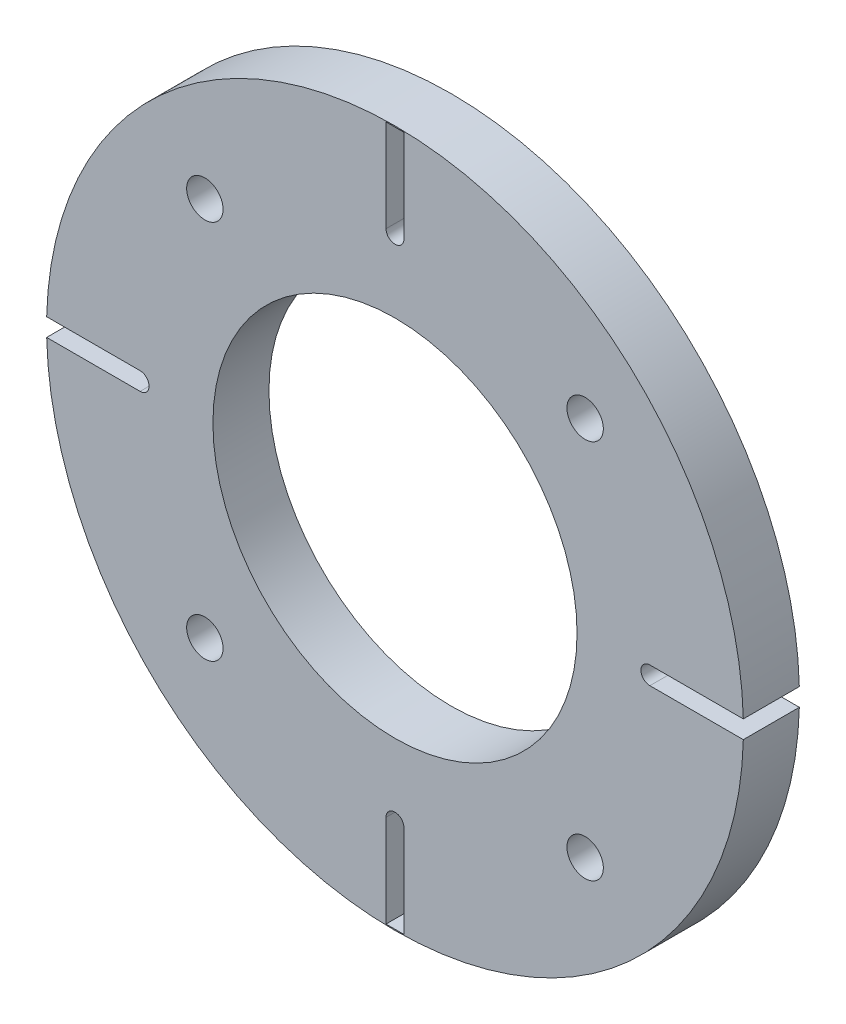
SolidWorks part; units mm, degrees
ref_plane "Ön Düzlem" through (0, 0, 0) normal (0, 0, 1) x (1, 0, 0)
ref_plane "Üst Düzlem" through (0, 0, 0) normal (0, 1, 0) x (1, 0, 0)
ref_plane "Sağ Düzlem" through (0, 0, 0) normal (1, 0, 0) x (0, 0, -1)
sketch "Çizim1" plane through (0, 0, 0) normal (0, 0, 1) x (1, 0, 0)
  circle A0 centre (0, 0) radius 62.2
  dimension "D1" = 124.4
extrude "Yükseklik-Ekstrüzyon1" add sketch "Çizim1" along normal blind 10
sketch "Çizim2" plane through (0, 0, 10) normal (0, 0, 1) x (1, 0, 0)
  circle A0 centre (0, 0) radius 32.5
extrude "Kes-Ekstrüzyon1" cut sketch "Çizim2" against normal blind 10
sketch "Çizim4" plane through (0, 0, 10) normal (0, 0, 1) x (1, 0, 0)
  line L0 (-62.2, 0) -> (62.2, 0) construction
  line L1 (1.6, -62) -> (1.6, -45.5)
  line L2 (0, -62.2) -> (0, 62.2) construction
  line L4 (-1.6, 62) -> (-1.6, 45.5)
  line L5 (1.6, 62) -> (1.6, 45.5)
  line L6 (-1.6, -62) -> (-1.6, -45.5)
  line L7 (-1.6, -62) -> (1.6, -62)
  line L8 (-1.6, 62) -> (1.6, 62)
  line L9 (62.2, 1.6) -> (62.2, -1.6)
  line L10 (62.2, 1.6) -> (45.5, 1.6)
  line L11 (62.2, -1.6) -> (45.5, -1.6)
  line L12 (-62.2, -1.6) -> (-45.5, -1.6)
  line L13 (-62.2, 1.6) -> (-45.5, 1.6)
  line L14 (-62.2, 1.6) -> (-62.2, -1.6)
  arc A0 (45.5, 1.6) -> (45.5, -1.6) centre (45.5, 0) ccw
  circle A1 centre (0, 0) radius 62.2 construction
  arc A2 (-1.6, 45.5) -> (1.6, 45.5) centre (0, 45.5) ccw
  arc A3 (-1.6, -45.5) -> (1.6, -45.5) centre (0, -45.5) cw
  arc A4 (-45.5, 1.6) -> (-45.5, -1.6) centre (-45.5, 0) cw
  point P10 (0, 0)
  point P13 (0, 62.2)
  point P16 (0, 0)
  point P21 (0, -62.2)
  point P23 (62.2, 0)
  point P31 (-62.2, 0)
  dimension "D2" = 1.6
  dimension "D1" = 16.5
  dimension "D3" = 3.2
extrude "Kes-Ekstrüzyon2" cut sketch "Çizim4" against normal blind 10
sketch "Çizim5" plane through (0, 0, 0) normal (0, 0, -1) x (-1, 0, 0)
  line L0 (0, 0) -> (33.9411, -33.9411) construction
  line L1 (64.0068, 0) -> (-64.0068, 0) construction
  line L2 (0, 62.3273) -> (0, -62.3273)
  circle A0 centre (33.9411, -33.9411) radius 3.25
  circle A1 centre (33.9411, 33.9411) radius 3.25
  circle A2 centre (-33.9411, 33.9411) radius 3.25
  circle A3 centre (-33.9411, -33.9411) radius 3.25
  point P7 (0, 0)
  point P12 (0, 0)
extrude "Kes-Ekstrüzyon3" cut sketch "Çizim5" against normal blind 10 contours A2 | A1 | A0 | A3
